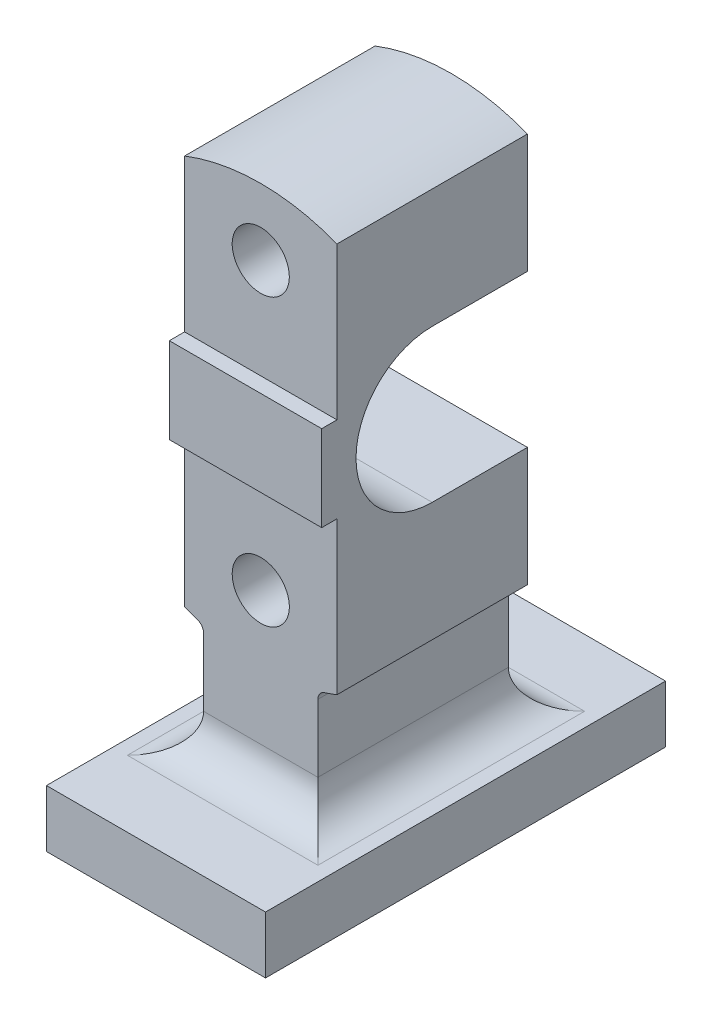
SolidWorks part; units mm, degrees
ref_plane "Front Plane" through (0, 0, 0) normal (0, 0, 1) x (1, 0, 0)
ref_plane "Top Plane" through (0, 0, 0) normal (0, 1, 0) x (1, 0, 0)
ref_plane "Right Plane" through (0, 0, 0) normal (1, 0, 0) x (0, 0, -1)
sketch "Sketch1" plane through (0, 0, 0) normal (0, 0, 1) x (1, 0, 0)
  line L0 (-40, 102.4695) -> (-40, -102.4695)
  line L1 (-30, -165) -> (30, -165)
  line L2 (40, 102.4695) -> (40, -102.4695)
  line L3 (0, -55) -> (0, 55) construction
  line L4 (55, 0) -> (-55, 0) construction
  line L5 (-30, -165) -> (-30, -109.5445)
  line L6 (30, -165) -> (30, -109.5445)
  arc A0 (-40, -102.4695) -> (-33.4783, -104.7817) centre (0, 0) ccw
  arc A1 (40, 102.4695) -> (-40, 102.4695) centre (0, 0) ccw
  circle A2 centre (0, 75) radius 15
  circle A3 centre (0, -75) radius 15
  arc A4 (33.4783, -104.7817) -> (40, -102.4695) centre (0, 0) ccw
  arc A5 (30, -109.5445) -> (33.4783, -104.7817) centre (35, -109.5445) cw
  arc A6 (-30, -109.5445) -> (-33.4783, -104.7817) centre (-35, -109.5445) ccw
  point P16 (0, -165)
  point P21 (30, -105.8301)
  dimension "D1" = 110
  dimension "D3" = 75
  dimension "D4" = 30
  dimension "D8" = 5
  dimension "D2" = 80
  dimension "D5" = 90
  dimension "D6" = 60
  dimension "D7" = 0
extrude "Boss-Extrude1" add sketch "Sketch1" along normal blind 100
sketch "Sketch2" plane through (0, 0, 100) normal (0, 0, 1) x (1, 0, 0)
  line L0 (0, -55) -> (0, 55) construction
  line L1 (-57.5, -195) -> (57.5, -195)
  line L2 (-57.5, -195) -> (-57.5, -165)
  line L3 (-57.5, -165) -> (57.5, -165)
  line L4 (57.5, -195) -> (57.5, -165)
  line L5 (-57.5, -195) -> (57.5, -165) construction
  line L6 (-57.5, -165) -> (57.5, -195) construction
  line L7 (-30, -165) -> (30, -165) construction
  point P0 (0, -180)
  dimension "D1" = 0
extrude "Boss-Extrude2" add sketch "Sketch2" along normal mid plane 210 from offset 50 offset against normal yes
fillet "Fillet1" radius 20 4 edges at (0, -165, 0) (-30, -165, 50) (30, -165, 50) (0, -165, 100)
sketch "Sketch3" plane through (0, 0, 100) normal (0, 0, 1) x (1, 0, 0)
  line L0 (40, -102.4695) -> (40, 102.4695) construction
  line L1 (-40, -22.5) -> (40, -22.5)
  line L2 (-40, -22.5) -> (-40, 22.5)
  line L3 (-40, 22.5) -> (40, 22.5)
  line L4 (40, -22.5) -> (40, 22.5)
  line L5 (-40, -22.5) -> (40, 22.5) construction
  line L6 (-40, 22.5) -> (40, -22.5) construction
  point P0 (0, 0)
extrude "Boss-Extrude3" add sketch "Sketch3" along normal blind 8
sketch "Sketch4" plane through (-40, 0, 0) normal (-1, 0, 0) x (0, 0, 1)
  line L0 (0, 102.4695) -> (0, -102.4695) construction
  line L1 (-70, -40) -> (50, -40)
  line L2 (-70, -40) -> (-70, 40)
  line L3 (-70, 40) -> (50, 40)
  arc A0 (50, 40) -> (50, -40) centre (50, 0) cw
  point P0 (0, 0)
  dimension "D1" = 50
extrude "Cut-Extrude1" cut sketch "Sketch4" against normal through all
